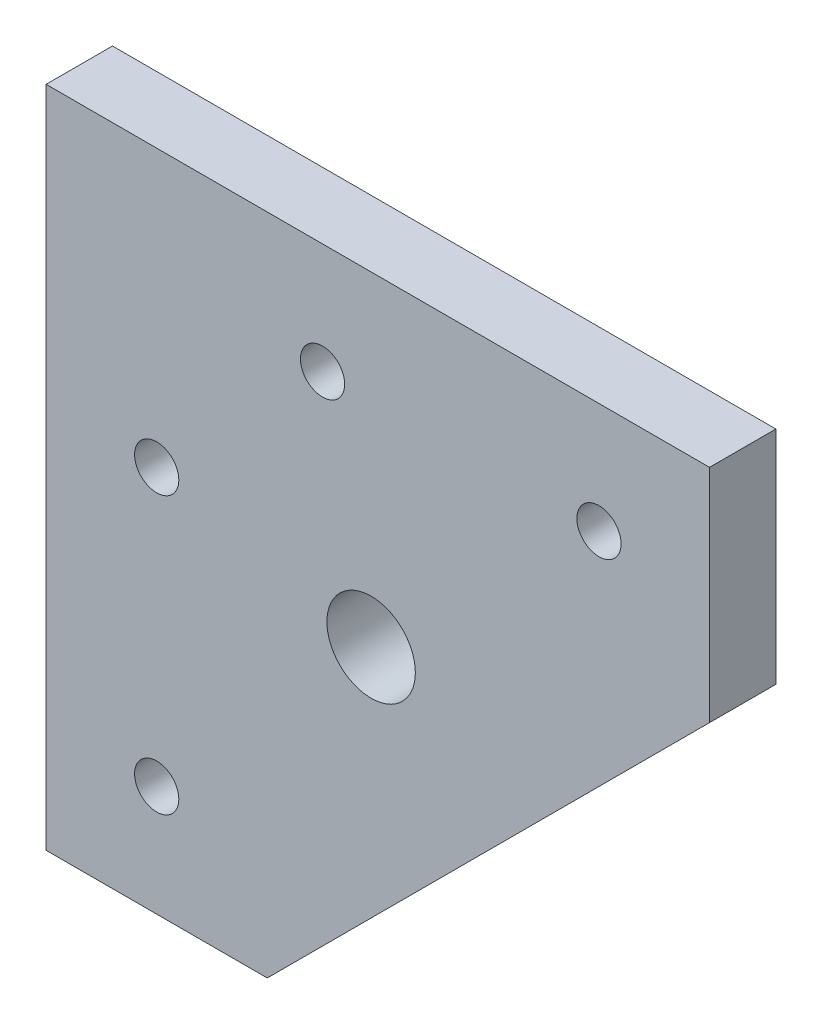
SolidWorks part; units mm, degrees
ref_plane "Front Plane" through (0, 0, 0) normal (0, 0, 1) x (1, 0, 0)
ref_plane "Top Plane" through (0, 0, 0) normal (0, 1, 0) x (1, 0, 0)
ref_plane "Right Plane" through (0, 0, 0) normal (1, 0, 0) x (0, 0, -1)
sketch "Sketch1" plane through (0, 0, 0) normal (0, 0, 1) x (1, 0, 0)
  line L0 (20, -60) -> (60, -20)
  line L1 (0, 0) -> (60, 0)
  line L2 (0, 0) -> (0, -60)
  line L3 (0, -60) -> (20, -60)
  line L4 (60, 0) -> (60, -20)
  line L5 (10, -60) -> (10, -50) construction
  line L6 (10, -50) -> (10, -25) construction
  line L7 (10, -25) -> (10, -10) construction
  line L8 (10, -10) -> (25, -10) construction
  line L9 (25, -10) -> (50, -10) construction
  line L10 (50, -10) -> (60, -10) construction
  line L11 (0, 0) -> (40, -40) construction
  circle A0 centre (50, -10) radius 2
  circle A1 centre (25, -10) radius 2
  circle A2 centre (10, -50) radius 2
  circle A3 centre (10, -25) radius 2
  circle A4 centre (29.3934, -29.3934) radius 4
  dimension "D3" = 4
  dimension "D8" = 8
  dimension "D9" = 15
  dimension "D1" = 60
  dimension "D2" = 20
  dimension "D4" = 10
  dimension "D5" = 25
  dimension "D6" = 25
  dimension "D7" = 10
extrude "Boss-Extrude1" add sketch "Sketch1" along normal blind 6
